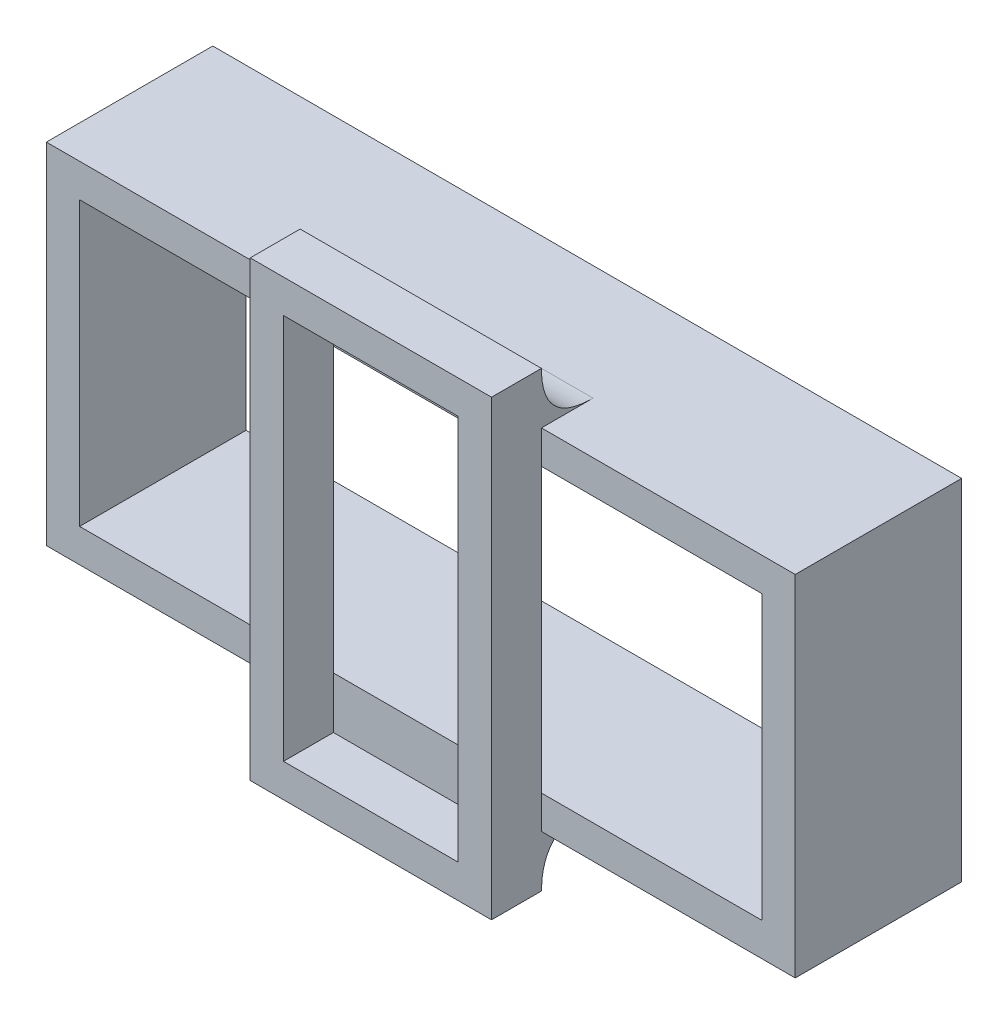
SolidWorks part; units mm, degrees
ref_plane "Płaszczyzna przednia" through (0, 0, 0) normal (0, 0, 1) x (1, 0, 0)
ref_plane "Płaszczyzna górna" through (0, 0, 0) normal (0, 1, 0) x (1, 0, 0)
ref_plane "Płaszczyzna prawa" through (0, 0, 0) normal (1, 0, 0) x (0, 0, -1)
sketch "Szkic1" plane through (0, 0, 0) normal (0, 0, 1) x (1, 0, 0)
  line L0 (-1.7455, 49.681) -> (39.2545, 32.681) construction
  line L1 (39.2545, 49.681) -> (-1.7455, 49.681)
  line L2 (39.2545, 49.681) -> (39.2545, 32.681)
  line L3 (39.2545, 32.681) -> (-1.7455, 32.681)
  line L4 (-1.7455, 49.681) -> (-1.7455, 32.681)
  line L6 (-3.7455, 30.681) -> (41.2545, 30.681)
  line L7 (-3.7455, 30.681) -> (-3.7455, 51.681)
  line L8 (-3.7455, 51.681) -> (41.2545, 51.681)
  line L9 (41.2545, 30.681) -> (41.2545, 51.681)
  line L10 (-3.7455, 30.681) -> (41.2545, 51.681) construction
  line L11 (-3.7455, 51.681) -> (41.2545, 30.681) construction
  point P4 (18.7545, 41.181)
extrude "Dodanie-wyciągnięcie1" add sketch "Szkic1" along normal blind 10
sketch "Szkic2" plane through (0, 0, 10) normal (0, 0, 1) x (1, 0, 0)
  line L0 (-1.7455, 49.681) -> (39.2545, 32.681) construction
  line L1 (-1.7455, 49.681) -> (-1.7455, 32.681) construction
  line L2 (-1.7455, 32.681) -> (39.2545, 32.681) construction
  line L4 (13.5045, 29.581) -> (24.0045, 29.581)
  line L5 (13.5045, 29.581) -> (13.5045, 52.781)
  line L6 (13.5045, 52.781) -> (24.0045, 52.781)
  line L7 (24.0045, 29.581) -> (24.0045, 52.781)
  line L8 (13.5045, 29.581) -> (24.0045, 52.781) construction
  line L9 (13.5045, 52.781) -> (24.0045, 29.581) construction
  line L10 (11.5045, 27.581) -> (26.0045, 27.581)
  line L11 (11.5045, 27.581) -> (11.5045, 54.781)
  line L12 (11.5045, 54.781) -> (26.0045, 54.781)
  line L13 (26.0045, 27.581) -> (26.0045, 54.781)
  line L14 (11.5045, 27.581) -> (26.0045, 54.781) construction
  line L15 (11.5045, 54.781) -> (26.0045, 27.581) construction
  point P6 (18.7545, 41.181)
  point P11 (18.7545, 41.181)
extrude "Dodanie-wyciągnięcie2" add sketch "Szkic2" along normal blind 3
sketch "Szkic3" plane through (26.0045, 0, 0) normal (1, 0, 0) x (0, 0, -1)
  line L0 (-10, 54.781) -> (-10, 51.681)
  line L1 (-10, 51.681) -> (-6.9, 51.681)
  line L2 (-10, 51.681) -> (0, 51.681) construction
  line L3 (-10, 27.581) -> (-10, 30.681)
  line L4 (-10, 30.681) -> (-6.9, 30.681)
  line L5 (-10, 30.681) -> (0, 30.681) construction
  line L6 (-10, 27.581) -> (-10, 30.681) construction
  line L7 (-10, 30.681) -> (-6.9, 30.681) construction
  line L8 (-6.9, 51.681) -> (-10, 51.681) construction
  line L9 (-10, 51.681) -> (-10, 54.781) construction
  spline S0 degree 2 poles (-10, 27.581) (-10, 30.681) (-6.9, 30.681) knots 0 0 0 1 1 1
  spline S1 degree 2 poles (-6.9, 51.681) (-10, 51.681) (-10, 54.781) knots 0 0 0 1 1 1
extrude "Dodanie-wyciągnięcie3" add sketch "Szkic3" against normal up to vertex
